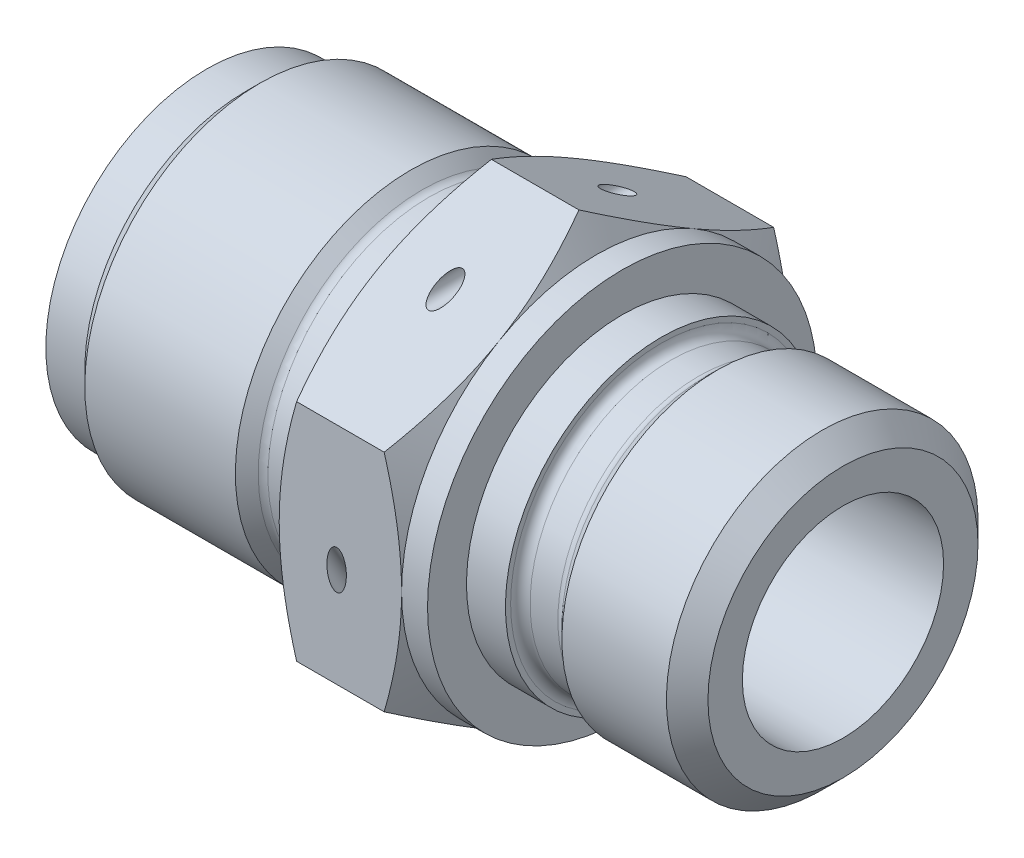
SolidWorks part; units mm, degrees
material "Бронза БрАМц9-2 ГОСТ 18175-78"
ref_plane "Спереди" through (0, 0, 0) normal (0, 0, 1) x (1, 0, 0)
ref_plane "Сверху" through (0, 0, 0) normal (0, 1, 0) x (1, 0, 0)
ref_plane "Справа" through (0, 0, 0) normal (1, 0, 0) x (0, 0, -1)
sketch "Эскиз1" plane through (0, 0, 0) normal (0, 0, 1) x (1, 0, 0)
  line L0 (0, 0) -> (-292.1333, 0) construction
  line L1 (0, 7.75) -> (-19.3, 7.75)
  line L2 (-19.3, 7.75) -> (-19.3, 3)
  line L3 (-19.3, 3) -> (-52, 3)
  line L4 (-52, 3) -> (-52, 6.75)
  line L5 (-51.75, 7) -> (-49, 7)
  line L6 (-49, 7) -> (-49, 12.4)
  line L7 (-49, 12.4) -> (-46, 12.4)
  line L8 (-46, 12.4) -> (-44.9, 13.5)
  line L9 (-44.9, 13.5) -> (-33.3, 13.5)
  line L10 (-33.3, 13.5) -> (-32.4197, 12.6197)
  line L11 (-31.8893, 12.4) -> (-29.75, 12.4)
  line L12 (-29, 13.15) -> (-29, 20)
  line L13 (-29, 20) -> (-19, 20)
  line L14 (-19, 20) -> (-19, 15)
  line L15 (-17, 12) -> (-14, 12)
  line L16 (-14, 12) -> (-14, 11.6)
  line L17 (-13.25, 10.85) -> (-11.1107, 10.85)
  line L18 (-10.5803, 11.0697) -> (-9.65, 12)
  line L19 (-9.65, 12) -> (-1.6, 12)
  line L20 (-1.6, 12) -> (0, 10.4)
  line L21 (0, 10.4) -> (0, 7.75)
  line L22 (-19, 15) -> (-17, 15)
  line L23 (-17, 15) -> (-17, 12)
  line L24 (-52, 6.75) -> (-51.75, 7)
  arc A0 (-29.75, 12.4) -> (-29, 13.15) centre (-29.75, 13.15) ccw
  arc A1 (-32.4197, 12.6197) -> (-31.8893, 12.4) centre (-31.8893, 13.15) ccw
  arc A2 (-11.1107, 10.85) -> (-10.5803, 11.0697) centre (-11.1107, 11.6) ccw
  arc A3 (-14, 11.6) -> (-13.25, 10.85) centre (-13.25, 11.6) ccw
  point P8 (-52, 7)
  point P28 (-29, 12.4)
  point P31 (-32.2, 12.4)
  point P34 (-10.8, 10.85)
  point P37 (-14, 10.85)
  dimension "D24" = 0.75
  dimension "D1" = 15.5
  dimension "D2" = 6
  dimension "D3" = 19.3
  dimension "D4" = 3
  dimension "D5" = 3
  dimension "d 1" = 14
  dimension "d 2" = 24.8
  dimension "d" = 27
  dimension "D9" = 45
  dimension "D10" = 45
  dimension "D11" = 1.6
  dimension "D12" = 24
  dimension "D13" = 21.7
  dimension "D14" = 3.2
  dimension "D15" = 17
  dimension "D16" = 14
  dimension "l" = 20
  dimension "D18" = 3.2
  dimension "D19" = 30
  dimension "D20" = 40
  dimension "L'" = 52
  dimension "D22" = 19
  dimension "D23" = 24
  dimension "D25" = 0.25
  dimension "D26" = 45
revolve "Повернуть1" add sketch "Эскиз1" angle 360 about L0
cosmetic thread "Условное изображение резьбы1" [suppressed] parameters "D2"=20.344
cosmetic thread "Условное изображение резьбы2" parameters "D2"=21.797
cosmetic thread "Условное изображение резьбы3" parameters "D2"=24.797
sketch "Эскиз2" plane through (-29, 0, 0) normal (-1, 0, 0) x (0, 0, 1)
  line L1 (0, 17.3205) -> (-15, 8.6603)
  line L2 (-15, 8.6603) -> (-15, -8.6603)
  line L3 (-15, -8.6603) -> (0, -17.3205)
  line L4 (0, -17.3205) -> (15, -8.6603)
  line L5 (15, -8.6603) -> (15, 8.6603)
  line L6 (15, 8.6603) -> (0, 17.3205)
  circle A0 centre (0, 0) radius 15 construction
  dimension "D1" = 30
extrude "Вырез-Вытянуть1" cut sketch "Эскиз2" against normal through all flip side to cut
sketch "Эскиз3" plane through (-19, 0, 0) normal (1, 0, 0) x (0, 0, -1)
  circle A0 centre (0, 0) radius 15 construction
  circle A1 centre (0, 0) radius 15
extrude "Вырез-Вытянуть2" cut sketch "Эскиз3" against normal through all draft 60 flip side to cut
sketch "Эскиз4" plane through (-29, 0, 0) normal (-1, 0, 0) x (0, 0, 1)
  circle A2 centre (0, 0) radius 14
  dimension "D1" = 28
extrude "Вырез-Вытянуть3" cut sketch "Эскиз4" against normal through all draft 60 flip side to cut
sketch "Эскиз5" plane through (0, 0, 0) normal (0, 0, 1) x (1, 0, 0)
  line L0 (-29, 14) -> (-29, -14) construction
  circle A0 centre (-24, 13.5) radius 0.75
  dimension "D2" = 1.5
  dimension "D1" = 5
  dimension "D3" = 13.5
extrude "Вырез-Вытянуть4" cut sketch "Эскиз5" against normal through all and the other way through all
pattern_circular "Круговой массив1" count 3 over 360 about axis through (0, 0, 0) along (1, 0, 0) of "Вырез-Вытянуть4"
